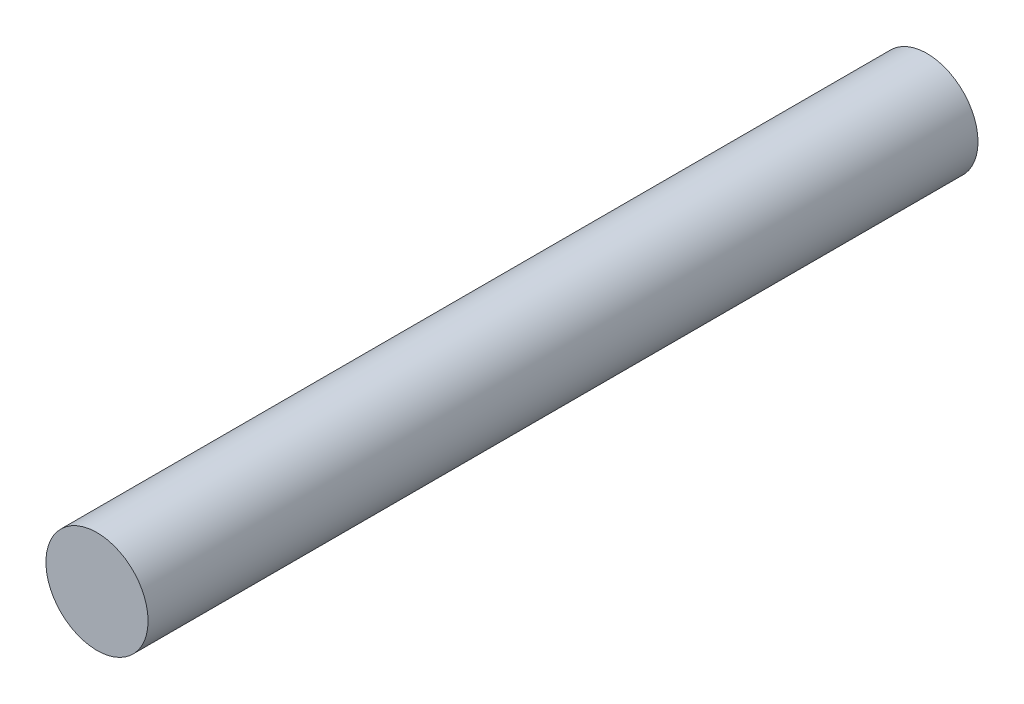
SolidWorks part; units mm, degrees
ref_plane "Front Plane" through (0, 0, 0) normal (0, 0, 1) x (1, 0, 0)
ref_plane "Top Plane" through (0, 0, 0) normal (0, 1, 0) x (1, 0, 0)
ref_plane "Right Plane" through (0, 0, 0) normal (1, 0, 0) x (0, 0, -1)
sketch "Sketch1" plane through (0, 0, 0) normal (0, 0, 1) x (1, 0, 0)
  circle A0 centre (0, 0) radius 4
  dimension "D1" = 8
extrude "Boss-Extrude1" add sketch "Sketch1" along normal mid plane 65
